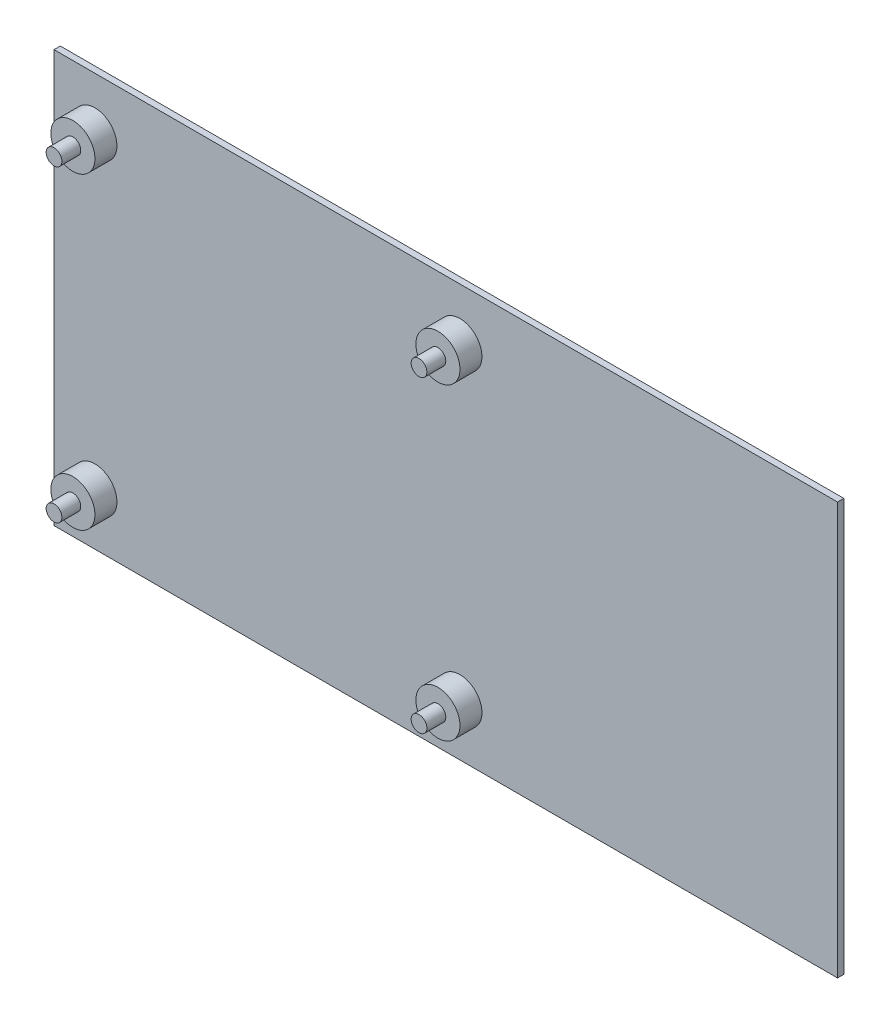
SolidWorks part; units mm, degrees
ref_plane "Front Plane" through (0, 0, 0) normal (0, 0, 1) x (1, 0, 0)
ref_plane "Top Plane" through (0, 0, 0) normal (0, 1, 0) x (1, 0, 0)
ref_plane "Right Plane" through (0, 0, 0) normal (1, 0, 0) x (0, 0, -1)
sketch "Sketch1" plane through (0, 0, 0) normal (0, 0, 1) x (1, 0, 0)
  line L1 (62.25, 32.75) -> (-62.25, 32.75)
  line L2 (62.25, 32.75) -> (62.25, -32.75)
  line L3 (62.25, -32.75) -> (-62.25, -32.75)
  line L4 (-62.25, 32.75) -> (-62.25, -32.75)
  line L5 (62.25, 32.75) -> (-62.25, -32.75) construction
  line L6 (62.25, -32.75) -> (-62.25, 32.75) construction
  point P0 (0, 0)
  dimension "D1" = 65.5
  dimension "D2" = 124.5
extrude "Boss-Extrude1" add sketch "Sketch1" along normal blind 1
sketch "Sketch2" plane through (0, 0, 1) normal (0, 0, 1) x (1, 0, 0)
  line L0 (-26.75, 0) -> (0, 0) construction
  line L1 (2.25, 24.5) -> (-55.75, 24.5) construction
  line L2 (2.25, 24.5) -> (2.25, -24.5) construction
  line L3 (2.25, -24.5) -> (-55.75, -24.5) construction
  line L4 (-55.75, 24.5) -> (-55.75, -24.5) construction
  line L5 (2.25, 24.5) -> (-55.75, -24.5) construction
  line L6 (2.25, -24.5) -> (-55.75, 24.5) construction
  line L7 (-62.25, 32.75) -> (-62.25, -32.75) construction
  circle A0 centre (-55.75, 24.5) radius 3.5
  circle A1 centre (2.25, 24.5) radius 3.5
  circle A2 centre (2.25, -24.5) radius 3.5
  circle A3 centre (-55.75, -24.5) radius 3.5
  point P0 (-26.75, 0)
  dimension "D4" = 7
  dimension "D1" = 58
  dimension "D2" = 49
  dimension "D3" = 6.5
extrude "Boss-Extrude2" add sketch "Sketch2" along normal blind 3.5
sketch "Sketch3" plane through (0, 0, 4.5) normal (0, 0, 1) x (1, 0, 0)
  circle A0 centre (-55.75, 24.5) radius 1.25
  circle A1 centre (2.25, 24.5) radius 1.25
  circle A2 centre (2.25, -24.5) radius 1.25
  circle A3 centre (-55.75, -24.5) radius 1.25
  dimension "D1" = 2.5
extrude "Boss-Extrude3" add sketch "Sketch3" along normal blind 3
